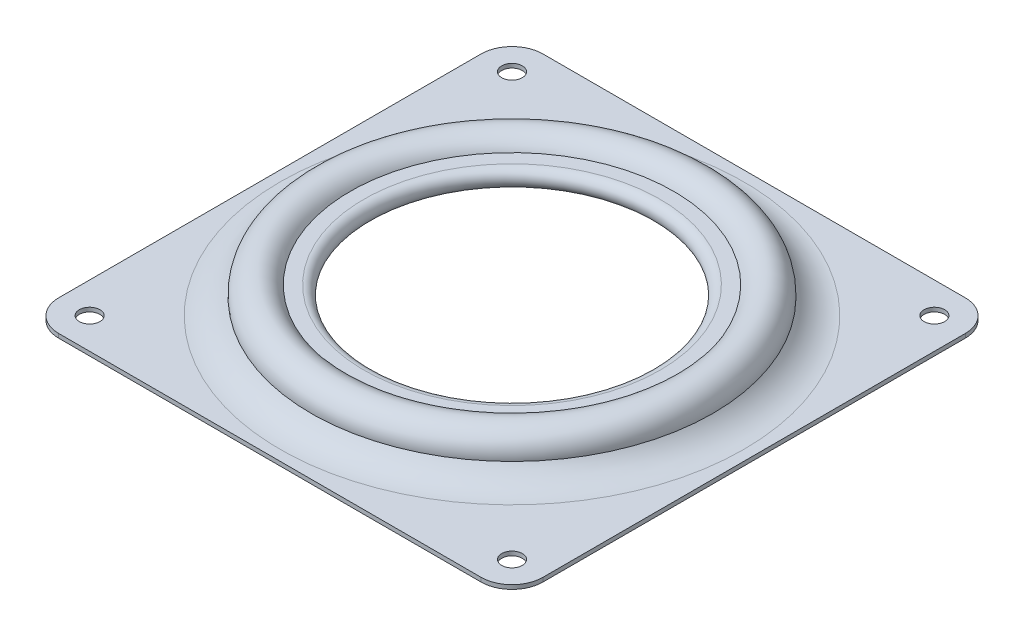
SolidWorks part; units mm, degrees
ref_plane "Plan de face" through (0, 0, 0) normal (0, 0, 1) x (1, 0, 0)
ref_plane "Plan de dessus" through (0, 0, 0) normal (0, 1, 0) x (1, 0, 0)
ref_plane "Plan de droite" through (0, 0, 0) normal (1, 0, 0) x (0, 0, -1)
sketch "Esquisse2" plane through (0, 0, 0) normal (0, 0, 1) x (1, 0, 0)
  line L0 (-65, 0) -> (-45, 0)
  line L1 (-65, 0) -> (-65, 0.8)
  line L2 (-65, 0.8) -> (-45, 0.8)
  line L3 (-31.4031, 2.5) -> (-28.75, 2.5)
  line L4 (-28.75, 6) -> (-31.4031, 6)
  line L5 (0, 0) -> (0, 6) construction
  arc A0 (-45, 0) -> (-38.0764, 1.6935) centre (-45, 15) ccw
  arc A1 (-45, 0.8) -> (-38.9779, 3.8297) centre (-45, 8.3) ccw
  arc A2 (-31.4031, 6) -> (-38.9779, 3.8297) centre (-35, 4.25) ccw
  arc A3 (-28.75, 2.5) -> (-28.75, 6) centre (-28.75, 4.25) ccw
  arc A4 (-38.0764, 1.6935) -> (-31.4031, 2.5) centre (-35, 4.25) ccw
  dimension "D1" = 0.8
  dimension "D3" = 4.25
  dimension "D4" = 4
  dimension "D5" = 70
  dimension "D7" = 54
  dimension "D9" = 15
  dimension "D10" = 7.5
  dimension "D2" = 130
  dimension "D6" = 3.5
  dimension "D8" = 90
revolve "Révolution1" add sketch "Esquisse2" angle 360 about L5
sketch "Esquisse3" plane through (0, 0, 0) normal (0, 1, 0) x (1, 0, 0)
  line L0 (-47, -41) -> (-47, 41)
  line L1 (-41, 47) -> (41, 47)
  line L2 (0, 47) -> (0, 0) construction
  line L3 (0, 0) -> (-47, 0) construction
  line L4 (-41, -47) -> (41, -47)
  line L5 (-45.2426, 45.2426) -> (0, 0) construction
  line L6 (47, -41) -> (47, 41)
  arc A0 (-47, 41) -> (-41, 47) centre (-41, 41) cw
  circle A1 centre (-41, 41) radius 2
  circle A2 centre (-41, -41) radius 2
  arc A3 (-47, -41) -> (-41, -47) centre (-41, -41) ccw
  arc A4 (47, -41) -> (41, -47) centre (41, -41) cw
  circle A5 centre (41, -41) radius 2
  circle A6 centre (41, 41) radius 2
  arc A7 (47, 41) -> (41, 47) centre (41, 41) ccw
  dimension "D1" = 94
  dimension "D2" = 127.9655
  dimension "D3" = 82
  dimension "D4" = 4
  dimension "D5" = 6
extrude "Enlèv. mat.-Extru.4" cut sketch "Esquisse3" along normal blind 10 flip side to cut
